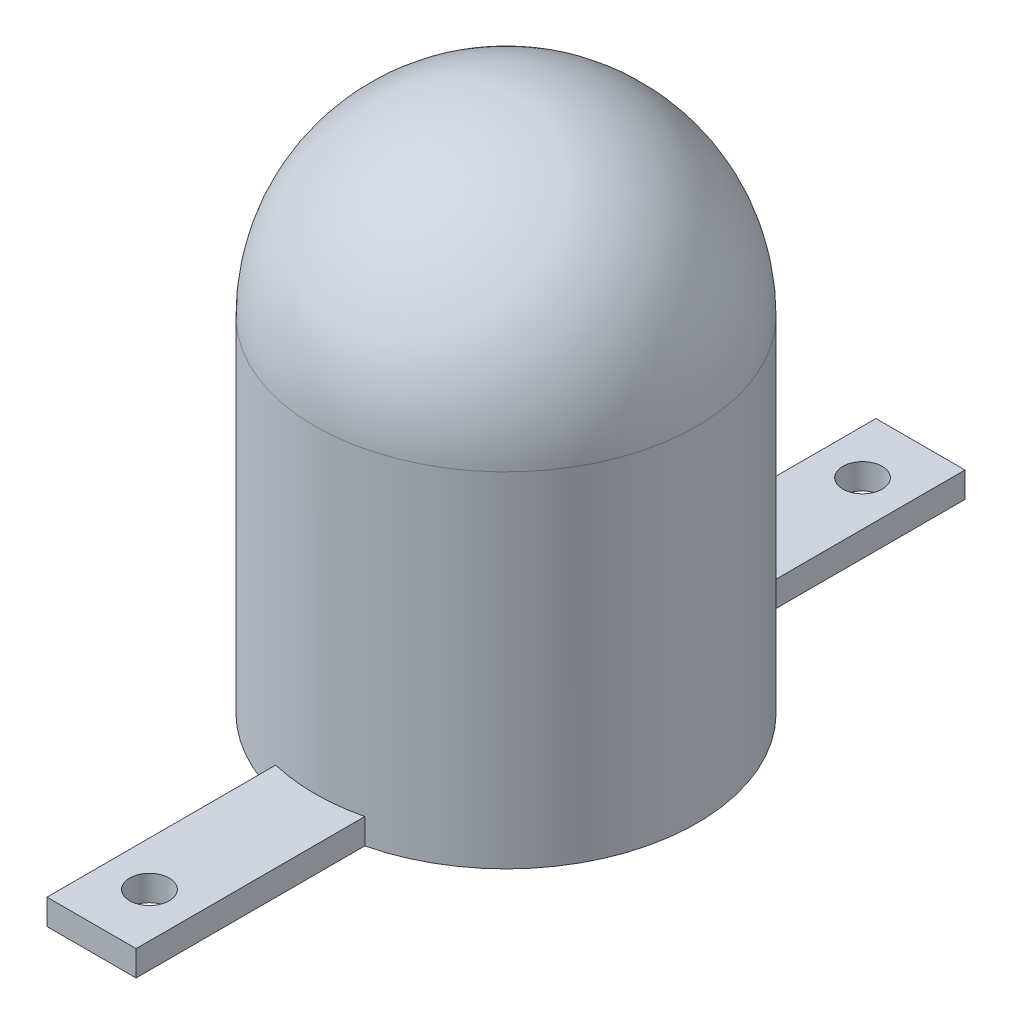
SolidWorks part; units mm, degrees
ref_plane "정면" through (0, 0, 0) normal (0, 0, 1) x (1, 0, 0)
ref_plane "윗면" through (0, 0, 0) normal (0, 1, 0) x (1, 0, 0)
ref_plane "우측면" through (0, 0, 0) normal (1, 0, 0) x (0, 0, -1)
sketch "Sketch1" plane through (0, 0, 0) normal (0, 1, 0) x (1, 0, 0)
  line L0 (-3.5, 32.55) -> (3.5, -32.55) construction
  line L1 (-3.5, 32.55) -> (3.5, 32.55)
  line L2 (-3.5, 32.55) -> (-3.5, -32.55)
  line L3 (-3.5, -32.55) -> (3.5, -32.55)
  line L4 (3.5, 32.55) -> (3.5, -32.55)
  point P4 (0, 0)
  dimension "D1" = 65.1
  dimension "D2" = 7
extrude "Boss-Extrude1" add sketch "Sketch1" along normal blind 2
ref_plane "Plane1" through (0, 27, 0) normal (0, 1, 0) x (1, 0, 0)
sketch "Sketch2" plane through (0, 27, 0) normal (0, 1, 0) x (1, 0, 0)
  line L0 (0, 15) -> (0, -15)
  arc A0 (0, -15) -> (0, 15) centre (0, 0) ccw
  dimension "D1" = 15
revolve "Revolve1" add sketch "Sketch2" angle 180 about L0
sketch "Sketch3" plane through (0, 27, 0) normal (0, -1, 0) x (1, 0, 0)
  circle A0 centre (0, 0) radius 15
extrude "Boss-Extrude2" add sketch "Sketch3" along normal through all
sketch "Sketch4" plane through (0, 2, 0) normal (0, 1, 0) x (1, 0, 0)
  line L0 (0, 25.6002) -> (0, -32.55) construction
  line L1 (-3.5, -32.55) -> (3.5, -32.55) construction
  line L2 (-3.6837, 0) -> (6.1395, 0) construction
  circle A0 centre (0, -28) radius 1.55
  circle A1 centre (0, 28) radius 1.55
  point P9 (0, 28)
  dimension "D1" = 3.1
  dimension "D2" = 28
extrude "Cut-Extrude1" cut sketch "Sketch4" against normal blind 2
